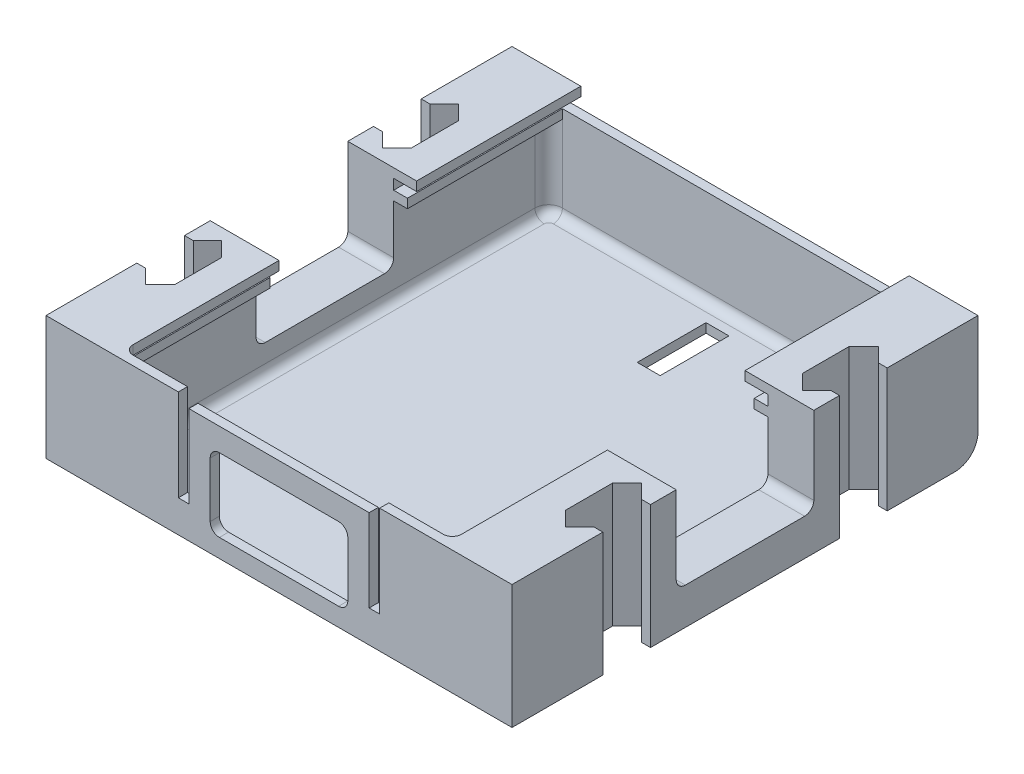
SolidWorks part; units mm, degrees
ref_plane "Front Plane" through (0, 0, 0) normal (0, 0, 1) x (1, 0, 0)
ref_plane "Top Plane" through (0, 0, 0) normal (0, 1, 0) x (1, 0, 0)
ref_plane "Right Plane" through (0, 0, 0) normal (1, 0, 0) x (0, 0, -1)
sketch "Sketch1" plane through (0, 0, 0) normal (0, 1, 0) x (1, 0, 0)
  line L1 (50.8, -50.8) -> (-50.8, -50.8)
  line L2 (50.8, -50.8) -> (50.8, 50.8)
  line L3 (50.8, 50.8) -> (-50.8, 50.8)
  line L4 (-50.8, -50.8) -> (-50.8, 50.8)
  line L5 (50.8, -50.8) -> (-50.8, 50.8) construction
  line L6 (50.8, 50.8) -> (-50.8, -50.8) construction
  point P0 (0, 0)
  dimension "D1" = 101.6
  dimension "6in" = 101.6
extrude "Boss-Extrude1" add sketch "Sketch1" along normal blind 25
shell "Shell1" thickness 2
sketch "Sketch2" plane through (0, 2, 0) normal (0, 1, 0) x (1, 0, 0)
  line L0 (50.8, 50.8) -> (-50.8, 50.8) construction
  line L1 (2.5, 29.8) -> (-2.5, 29.8)
  line L2 (2.5, 29.8) -> (2.5, 44.8)
  line L3 (2.5, 44.8) -> (-2.5, 44.8)
  line L4 (-2.5, 29.8) -> (-2.5, 44.8)
  line L5 (2.5, 29.8) -> (-2.5, 44.8) construction
  line L6 (2.5, 44.8) -> (-2.5, 29.8) construction
  line L7 (-50.8, 50.8) -> (-50.8, -50.8) construction
  point P0 (0, 37.3)
  dimension "D1" = 5
  dimension "D2" = 15
  dimension "D3" = 50.8
  dimension "D4" = 6
extrude "Cut-Extrude1" cut sketch "Sketch2" against normal blind 25
sketch "Sketch3" plane through (50.8, 0, 0) normal (1, 0, 0) x (0, 0, -1)
  line L0 (-50.8, 25) -> (50.8, 25) construction
  line L1 (-15, 42) -> (15, 42)
  line L2 (-15, 42) -> (-15, 10)
  line L3 (-13, 8) -> (13, 8)
  line L4 (15, 42) -> (15, 10)
  line L5 (-15, 42) -> (15, 8) construction
  line L6 (-15, 8) -> (15, 42) construction
  arc A0 (-15, 10) -> (-13, 8) centre (-13, 10) ccw
  arc A1 (13, 8) -> (15, 10) centre (13, 10) ccw
  point P0 (0, 25)
  dimension "D3" = 2
  dimension "D1" = 30
  dimension "D2" = 17
extrude "Cut-Extrude2" cut sketch "Sketch3" against normal through all
fillet "Fillet2" radius 3 4 edges at (40.8, 13.5, -48.8) (40.8, 13.5, 48.8) (-40.8, 13.5, 48.8) (-40.8, 13.5, -48.8)
fillet "Fillet3" radius 2 8 edges at (39.9213, 2, 47.9213) (0, 2, 48.8) (-39.9213, 2, 47.9213) (-40.8, 2, 0) (-39.9213, 2, -47.9213) (0, 2, -48.8) (39.9213, 2, -47.9213) (40.8, 2, 0)
sketch "Sketch7" plane through (0, 25, 0) normal (0, 1, 0) x (1, 0, 0)
  line L0 (50.8, -30.8) -> (48.8, -30.8) construction
  line L1 (50.8, -50.8) -> (50.8, -15) construction
  line L2 (48.8, -30.8) -> (45.8, -33.8) construction
  line L3 (45.8, -33.8) -> (42.8, -30.8) construction
  line L4 (42.8, -30.8) -> (42.8, -20.8) construction
  line L5 (42.8, -20.8) -> (45.8, -17.8) construction
  line L6 (45.8, -17.8) -> (48.8, -20.8) construction
  line L7 (48.8, -20.8) -> (50.8, -20.8) construction
  line L8 (50.8, -20.8) -> (50.8, -30.8) construction
  line L9 (0, 0) -> (50.8, 0) construction
  line L10 (0, 0) -> (0, -50.8) construction
  line L11 (-50.8, -50.8) -> (50.8, -50.8) construction
  line L12 (-50.8, -20.8) -> (-50.8, -30.8) construction
  line L13 (-48.8, -20.8) -> (-50.8, -20.8) construction
  line L14 (-45.8, -17.8) -> (-48.8, -20.8) construction
  line L15 (-42.8, -20.8) -> (-45.8, -17.8) construction
  line L16 (-42.8, -30.8) -> (-42.8, -20.8) construction
  line L17 (-45.8, -33.8) -> (-42.8, -30.8) construction
  line L18 (-48.8, -30.8) -> (-45.8, -33.8) construction
  line L19 (-50.8, -30.8) -> (-48.8, -30.8) construction
  line L20 (-50.8, 30.8) -> (-48.8, 30.8) construction
  line L21 (-48.8, 30.8) -> (-45.8, 33.8) construction
  line L22 (-45.8, 33.8) -> (-42.8, 30.8) construction
  line L23 (-42.8, 30.8) -> (-42.8, 20.8) construction
  line L24 (-42.8, 20.8) -> (-45.8, 17.8) construction
  line L25 (-45.8, 17.8) -> (-48.8, 20.8) construction
  line L26 (-48.8, 20.8) -> (-50.8, 20.8) construction
  line L27 (-50.8, 20.8) -> (-50.8, 30.8) construction
  line L28 (50.8, 20.8) -> (50.8, 30.8) construction
  line L29 (48.8, 20.8) -> (50.8, 20.8) construction
  line L30 (45.8, 17.8) -> (48.8, 20.8) construction
  line L31 (42.8, 20.8) -> (45.8, 17.8) construction
  line L32 (42.8, 30.8) -> (42.8, 20.8) construction
  line L33 (45.8, 33.8) -> (42.8, 30.8) construction
  line L34 (48.8, 30.8) -> (45.8, 33.8) construction
  line L35 (50.8, 30.8) -> (48.8, 30.8) construction
  line L36 (51, -31) -> (48.8828, -31)
  line L37 (48.8828, -31) -> (45.8, -34.0828)
  line L38 (45.8, -34.0828) -> (42.6, -30.8828)
  line L39 (42.6, -30.8828) -> (42.6, -20.7172)
  line L40 (42.6, -20.7172) -> (45.8, -17.5172)
  line L41 (45.8, -17.5172) -> (48.8828, -20.6)
  line L42 (48.8828, -20.6) -> (51, -20.6)
  line L43 (51, -20.6) -> (51, -31)
  line L44 (-51, -20.6) -> (-51, -31)
  line L45 (-51, -31) -> (-48.8828, -31)
  line L46 (-48.8828, -31) -> (-45.8, -34.0828)
  line L47 (-45.8, -34.0828) -> (-42.6, -30.8828)
  line L48 (-42.6, -30.8828) -> (-42.6, -20.7172)
  line L49 (-42.6, -20.7172) -> (-45.8, -17.5172)
  line L50 (-45.8, -17.5172) -> (-48.8828, -20.6)
  line L51 (-48.8828, -20.6) -> (-51, -20.6)
  line L52 (-51, 31) -> (-48.8828, 31)
  line L53 (-48.8828, 31) -> (-45.8, 34.0828)
  line L54 (-45.8, 34.0828) -> (-42.6, 30.8828)
  line L55 (-42.6, 30.8828) -> (-42.6, 20.7172)
  line L56 (-42.6, 20.7172) -> (-45.8, 17.5172)
  line L57 (-45.8, 17.5172) -> (-48.8828, 20.6)
  line L58 (-48.8828, 20.6) -> (-51, 20.6)
  line L59 (-51, 20.6) -> (-51, 31)
  line L60 (51, 20.6) -> (51, 31)
  line L61 (51, 31) -> (48.8828, 31)
  line L62 (48.8828, 31) -> (45.8, 34.0828)
  line L63 (45.8, 34.0828) -> (42.6, 30.8828)
  line L64 (42.6, 30.8828) -> (42.6, 20.7172)
  line L65 (42.6, 20.7172) -> (45.8, 17.5172)
  line L66 (45.8, 17.5172) -> (48.8828, 20.6)
  line L67 (48.8828, 20.6) -> (51, 20.6)
  point P40 (50.8, -25.8)
  dimension "D1" = 25
  dimension "D2" = 10
  dimension "D3" = 2
  dimension "D4" = 8
  dimension "D5" = 135
  dimension "D6" = 0.2
  dimension "D7" = 0.2
  dimension "D8" = 0.2
  dimension "D9" = 0.2
extrude "Cut-Extrude4" cut sketch "Sketch7" against normal through all
sketch "Sketch8" plane through (0, 0, 0) normal (1, 0, 0) x (0, 0, -1)
  line L0 (-45.8, 25) -> (-45.8, 21)
  line L1 (-31, 25) -> (-50.8, 25) construction
  line L2 (-42.3, 17.5) -> (-36.3, 17.5)
  line L3 (-36.3, 17.5) -> (-36.3, 20)
  line L4 (-36.3, 20) -> (-42.3, 20)
  line L5 (-43.3, 21) -> (-43.3, 25)
  line L6 (-43.3, 25) -> (-45.8, 25)
  line L7 (-50.8, 25) -> (-50.8, 0) construction
  arc A0 (-45.8, 21) -> (-42.3, 17.5) centre (-42.3, 21) ccw
  arc A1 (-42.3, 20) -> (-43.3, 21) centre (-42.3, 21) cw
  dimension "D1" = 3.5
  dimension "D2" = 1
  dimension "D3" = 2.5
  dimension "D4" = 2.5
  dimension "D5" = 4
  dimension "D6" = 6
  dimension "D7" = 5
sketch "Sketch11" plane through (0, 0, -50.8) normal (0, 0, -1) x (-1, 0, 0)
  line L0 (-21.95, 25) -> (-21.95, 7)
  line L1 (-50.8, 25) -> (50.8, 25) construction
  line L2 (-21.95, 7) -> (-19.65, 7)
  line L3 (-19.65, 7) -> (-19.65, 25)
  line L4 (-19.65, 25) -> (-21.95, 25)
  line L6 (-50.8, 25) -> (-50.8, 0) construction
  line L7 (0, 13.75) -> (0, -13.75) construction
  line L8 (19.65, 25) -> (21.95, 25)
  line L9 (19.65, 7) -> (19.65, 25)
  line L10 (21.95, 7) -> (19.65, 7)
  line L11 (21.95, 25) -> (21.95, 7)
  line L13 (-13, 4) -> (13, 4)
  line L14 (-15, 6) -> (-15, 18)
  line L15 (-13, 20) -> (13, 20)
  line L16 (15, 6) -> (15, 18)
  line L17 (-15, 4) -> (15, 20) construction
  line L18 (-15, 20) -> (15, 4) construction
  line L19 (50.8, 0) -> (-50.8, 0) construction
  arc A0 (13, 4) -> (15, 6) centre (13, 6) ccw
  arc A1 (-13, 4) -> (-15, 6) centre (-13, 6) cw
  arc A2 (-15, 18) -> (-13, 20) centre (-13, 18) cw
  arc A3 (13, 20) -> (15, 18) centre (13, 18) cw
  point P4 (-20.8, 7)
  point P15 (0, 12)
  dimension "D4" = 2
  dimension "D1" = 2.3
  dimension "D2" = 30
  dimension "D3" = 18
  dimension "D5" = 16
  dimension "D6" = 4
  dimension "D7" = 30
extrude "Cut-Extrude7" cut sketch "Sketch11" against normal through all from surface at -99.6 starting at face at (0, 14.5, 48.8)
sketch "Sketch12" plane through (0, 0, -50.8) normal (0, 0, -1) x (-1, 0, 0)
  line L0 (-40.8, 25) -> (-40.8, 22.75)
  line L1 (-50.8, 25) -> (50.8, 25) construction
  line L2 (-40.8, 22.75) -> (40.8, 22.75)
  line L3 (40.8, 22.75) -> (40.8, 25)
  line L4 (-50.8, 25) -> (50.8, 25) construction
  line L5 (40.8, 25) -> (-40.8, 25)
  line L6 (-40.8, 25) -> (-40.8, 4) construction
  line L7 (40.8, 25) -> (40.8, 4) construction
  dimension "D1" = 2.25
extrude "Cut-Extrude8" cut sketch "Sketch12" against normal blind 10
sketch "Sketch13" plane through (0, 22.75, 0) normal (0, 1, 0) x (1, 0, 0)
  line L0 (40.8, 45.8) -> (40.8, 15)
  line L1 (40.8, 15) -> (37.8, 15)
  line L2 (37.8, 15) -> (37.8, 48.8)
  line L3 (40.8, -45.8) -> (40.8, -15)
  line L4 (40.8, -15) -> (37.8, -15)
  line L5 (37.8, -15) -> (37.8, -48.8)
  arc A0 (37.8, -48.8) -> (40.8, -45.8) centre (37.8, -45.8) ccw construction
  arc A1 (40.8, 45.8) -> (37.8, 48.8) centre (37.8, 45.8) ccw construction
  arc A2 (37.8, -48.8) -> (40.8, -45.8) centre (37.8, -45.8) ccw
  arc A3 (40.8, 45.8) -> (37.8, 48.8) centre (37.8, 45.8) ccw
  point P6 (40.8, 19.7313)
  point P11 (40.8, 15)
  point P15 (40.8, -15)
extrude "Boss-Extrude2" add sketch "Sketch13" against normal blind 2
sketch "Sketch14" plane through (0, 25, 0) normal (0, 1, 0) x (1, 0, 0)
  line L1 (50.8, 50.8) -> (35.8, 50.8)
  line L2 (35.8, 50.8) -> (35.8, 15)
  line L3 (35.8, 15) -> (50.8, 15)
  line L4 (40.8, 15) -> (40.8, 50.8) construction
  line L6 (21.95, -50.8) -> (21.95, -48.8) construction
  line L7 (21.95, -50.8) -> (50.8, -50.8) construction
  line L9 (21.95, -50.8) -> (21.95, -48.8)
  line L10 (21.95, -50.8) -> (50.8, -50.8)
  line L12 (50.8, 50.8) -> (40.8, 50.8)
  line L13 (40.8, 50.8) -> (40.8, 15)
  line L14 (40.8, 15) -> (50.8, 15)
  line L15 (50.8, 15) -> (50.8, 20.6)
  line L16 (50.8, 20.6) -> (48.8828, 20.6)
  line L17 (48.8828, 20.6) -> (45.8, 17.5172)
  line L18 (45.8, 17.5172) -> (42.6, 20.7172)
  line L19 (42.6, 20.7172) -> (42.6, 30.8828)
  line L20 (42.6, 30.8828) -> (45.8, 34.0828)
  line L21 (45.8, 34.0828) -> (48.8828, 31)
  line L22 (48.8828, 31) -> (50.8, 31)
  line L23 (50.8, 31) -> (50.8, 50.8)
  line L27 (50.8, 15) -> (50.8, 20.6)
  line L28 (50.8, 20.6) -> (48.8828, 20.6)
  line L29 (48.8828, 20.6) -> (45.8, 17.5172)
  line L30 (45.8, 17.5172) -> (42.6, 20.7172)
  line L31 (42.6, 20.7172) -> (42.6, 30.8828)
  line L32 (42.6, 30.8828) -> (45.8, 34.0828)
  line L33 (45.8, 34.0828) -> (48.8828, 31)
  line L34 (48.8828, 31) -> (50.8, 31)
  line L35 (50.8, 31) -> (50.8, 50.8)
  line L36 (35.8, -15) -> (50.8, -15)
  line L37 (35.8, -15) -> (35.8, -48.8)
  line L38 (21.95, -48.8) -> (21.95, -50.8)
  line L39 (21.95, -50.8) -> (50.8, -50.8)
  line L40 (50.8, -50.8) -> (50.8, -31)
  line L41 (50.8, -31) -> (48.8828, -31)
  line L42 (48.8828, -31) -> (45.8, -34.0828)
  line L43 (45.8, -34.0828) -> (42.6, -30.8828)
  line L44 (42.6, -30.8828) -> (42.6, -20.7172)
  line L45 (42.6, -20.7172) -> (45.8, -17.5172)
  line L46 (45.8, -17.5172) -> (48.8828, -20.6)
  line L47 (48.8828, -20.6) -> (50.8, -20.6)
  line L48 (50.8, -20.6) -> (50.8, -15)
  line L49 (50.8, -15) -> (40.8, -15)
  line L50 (40.8, -15) -> (40.8, -45.8)
  line L51 (37.8, -48.8) -> (21.95, -48.8)
  line L54 (50.8, -50.8) -> (50.8, -31)
  line L55 (50.8, -31) -> (48.8828, -31)
  line L56 (48.8828, -31) -> (45.8, -34.0828)
  line L57 (45.8, -34.0828) -> (42.6, -30.8828)
  line L58 (42.6, -30.8828) -> (42.6, -20.7172)
  line L59 (42.6, -20.7172) -> (45.8, -17.5172)
  line L60 (45.8, -17.5172) -> (48.8828, -20.6)
  line L61 (48.8828, -20.6) -> (50.8, -20.6)
  line L62 (50.8, -20.6) -> (50.8, -15)
  line L66 (21.95, -48.8) -> (37.8, -48.8) construction
  line L67 (35.8, -48.8) -> (21.95, -48.8)
  arc A1 (37.8, -48.8) -> (40.8, -45.8) centre (37.8, -45.8) ccw
  dimension "D3" = 5
  dimension "D1" = 0
  dimension "D2" = 0
extrude "Boss-Extrude3" add sketch "Sketch14" along normal blind 2
fillet "Fillet4" radius 2 1 edges at (35.8, 26, 48.8)
mirror "Mirror1" about plane through (0, 0, 0) normal (1, 0, 0) of "Boss-Extrude2", "Boss-Extrude3", "Fillet4"
fillet "Fillet5" radius 5 1 edges at (0, 0, -50.8)
